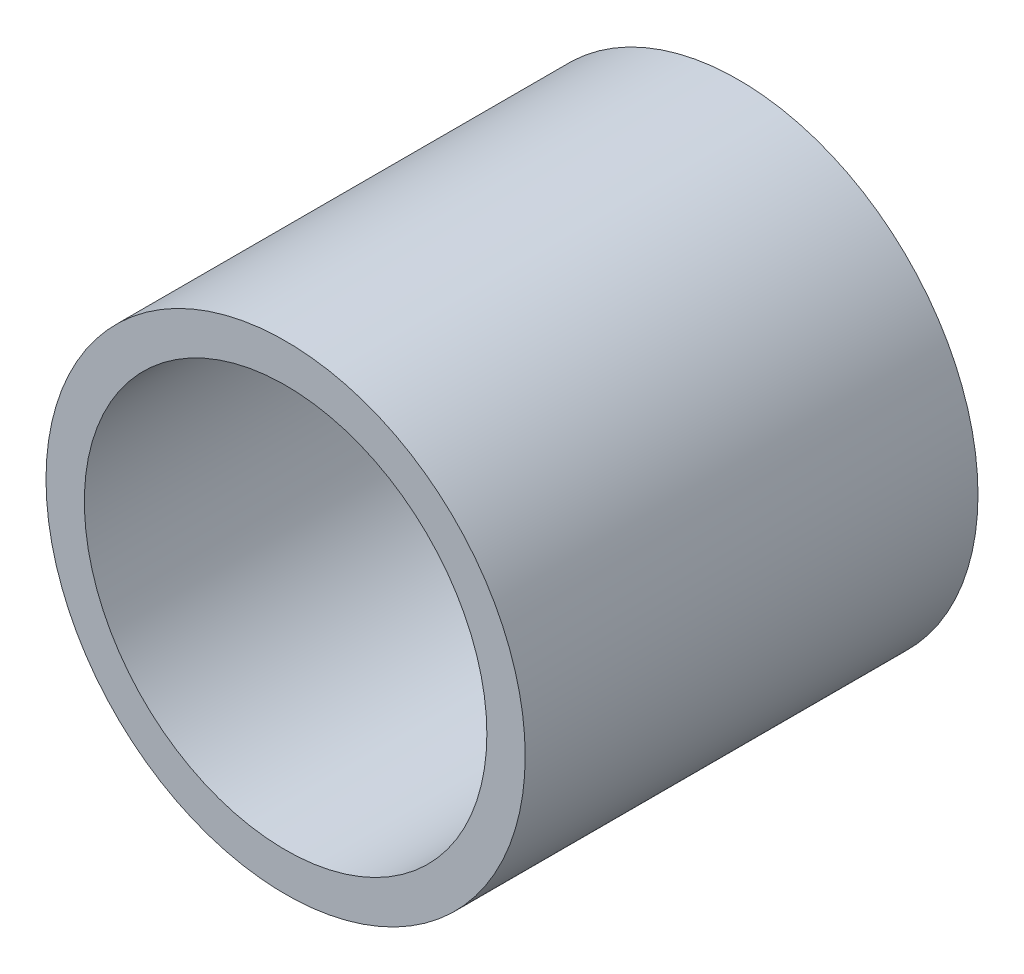
SolidWorks part; units mm, degrees
material "6061-T6 (SS)"
ref_plane "Front Plane" through (0, 0, 0) normal (0, 0, 1) x (1, 0, 0)
ref_plane "Top Plane" through (0, 0, 0) normal (0, 1, 0) x (1, 0, 0)
ref_plane "Right Plane" through (0, 0, 0) normal (1, 0, 0) x (0, 0, -1)
sketch "Sketch1" plane through (0, 0, 0) normal (0, 0, 1) x (1, 0, 0)
  circle A0 centre (0, 0) radius 3.175
  circle A1 centre (0, 0) radius 2.667
  dimension "D1" = 6.35
  dimension "D2" = 0.508
extrude "Boss-Extrude1" add sketch "Sketch1" along normal blind 6
